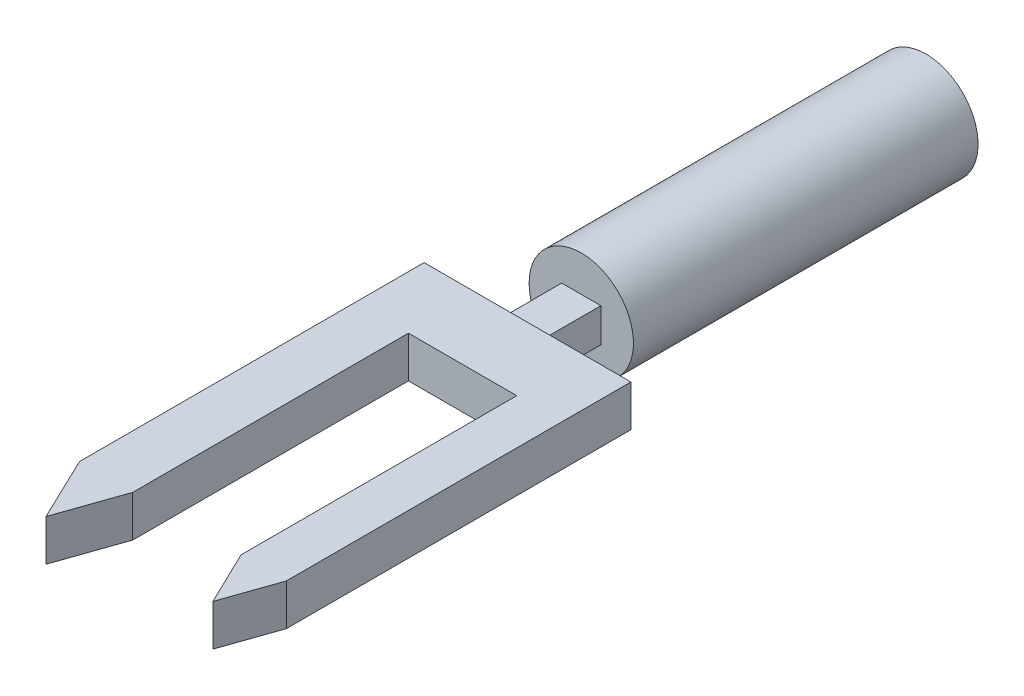
SolidWorks part; units mm, degrees
ref_plane "Front Plane" through (0, 0, 0) normal (0, 0, 1) x (1, 0, 0)
ref_plane "Top Plane" through (0, 0, 0) normal (0, 1, 0) x (1, 0, 0)
ref_plane "Right Plane" through (0, 0, 0) normal (1, 0, 0) x (0, 0, -1)
sketch "Sketch1" plane through (0, 0, 0) normal (0, 1, 0) x (1, 0, 0)
  line L0 (-7.4017, 0) -> (7.5983, 0)
  line L1 (-7.4017, 0) -> (-7.4017, -25)
  line L2 (7.5983, 0) -> (7.5983, -25)
  line L3 (7.5983, -25) -> (6.2227, -28.9454)
  line L4 (6.2227, -28.9454) -> (4.3172, -25)
  line L5 (4.3172, -25) -> (4.3172, -5)
  line L6 (4.3172, -5) -> (-3.5371, -5)
  line L7 (-3.5371, -5) -> (-3.5371, -25)
  line L8 (-3.5371, -25) -> (-5.1639, -29.6659)
  line L9 (-7.4017, -25) -> (-5.1639, -29.6659)
  dimension "D1" = 15
  dimension "D2" = 25
  dimension "D3" = 25
  dimension "D4" = 20
extrude "Boss-Extrude1" add sketch "Sketch1" along normal blind 3
sketch "Sketch2" plane through (0, 0, 0) normal (0, 0, -1) x (-1, 0, 0)
  line L1 (-1.4212, 2.7042) -> (1.4212, 2.7042)
  line L2 (-1.4212, 2.7042) -> (-1.4212, 0.2473)
  line L3 (-1.4212, 0.2473) -> (1.4212, 0.2473)
  line L4 (1.4212, 2.7042) -> (1.4212, 0.2473)
  line L5 (-1.4212, 2.7042) -> (1.4212, 0.2473) construction
  line L6 (-1.4212, 0.2473) -> (1.4212, 2.7042) construction
  point P0 (0, 1.4758)
extrude "Boss-Extrude2" add sketch "Sketch2" along normal blind 4
sketch "Sketch3" plane through (0, 0, -4) normal (0, 0, -1) x (-1, 0, 0)
  circle A0 centre (0, 1.5242) radius 3.7853
extrude "Boss-Extrude3" add sketch "Sketch3" along normal blind 25
